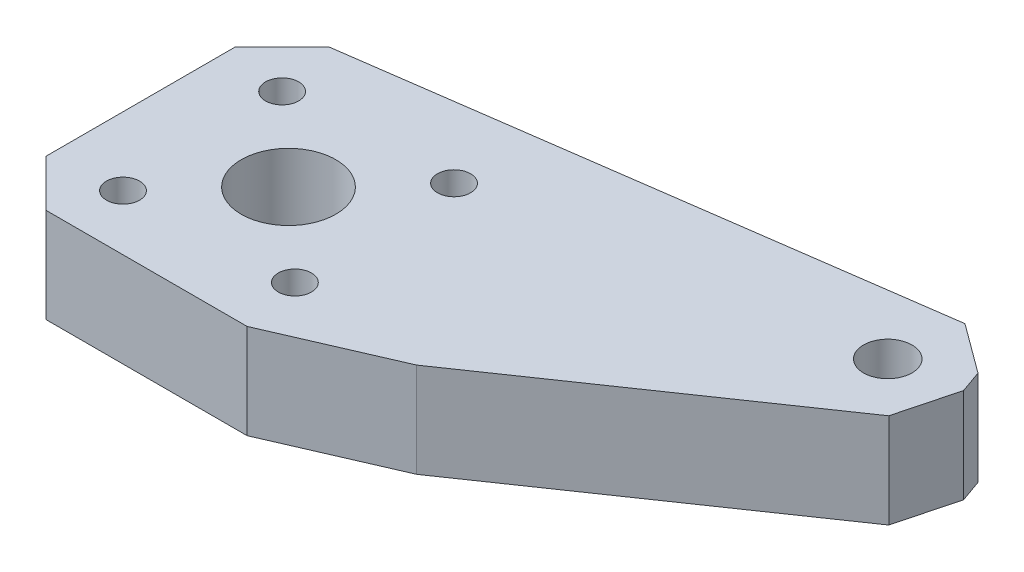
SolidWorks part; units mm, degrees
ref_plane "前视基准面" through (0, 0, 0) normal (0, 0, 1) x (1, 0, 0)
ref_plane "上视基准面" through (0, 0, 0) normal (0, 1, 0) x (1, 0, 0)
ref_plane "右视基准面" through (0, 0, 0) normal (1, 0, 0) x (0, 0, -1)
sketch "草图1" plane through (0, 0, 0) normal (0, 1, 0) x (1, 0, 0)
  line L0 (0, 0) -> (-3.9598, 3.9598)
  line L1 (-3.9598, 3.9598) -> (-3.9598, 19.9598)
  line L2 (-3.9598, 19.9598) -> (0, 23.9196)
  line L3 (0, 23.9196) -> (47.1368, 30.5442)
  line L4 (47.1368, 30.5442) -> (51.3094, 27.4747)
  line L5 (51.3094, 27.4747) -> (51.9765, 25.5893)
  line L6 (51.9765, 25.5893) -> (50.6628, 20.5786)
  line L7 (50.6628, 20.5786) -> (26.999, 4.3394)
  line L8 (26.999, 4.3394) -> (17, 0)
  line L9 (17, 0) -> (0, 0)
  line L10 (51.6429, 26.532) -> (46.4579, 24.6974) construction
  line L11 (-3.9598, 11.9598) -> (21.0402, 11.9598) construction
  line L12 (-1.9799, 21.9397) -> (2.8765, 17.0833) construction
  circle A0 centre (8.5402, 11.9598) radius 4
  circle A1 centre (46.4579, 24.6974) radius 2.05
  circle A2 centre (1.275, 18.6848) radius 1.4
  circle A3 centre (15.2652, 19.225) radius 1.4
  circle A4 centre (15.8054, 5.2348) radius 1.4
  circle A5 centre (1.8152, 4.6946) radius 1.4
  point P31 (8.5402, 11.9598)
  dimension "D15" = 40
  dimension "D17" = 12.5
  dimension "D20" = 4.1
  dimension "D21" = 8
  dimension "D22" = 9.9
  dimension "D23" = 2.8
  dimension "D2" = 16
  dimension "D3" = 5.6
  dimension "D4" = 5.6
  dimension "D5" = 17
  dimension "D6" = 47.6
  dimension "D7" = 10.9
  dimension "D8" = 28.7
  dimension "D9" = 5.18
  dimension "D10" = 2
  dimension "D11" = 5.18
  dimension "D12" = 45
  dimension "D13" = 45
  dimension "D14" = 45
  dimension "D16" = 143
  dimension "D18" = 5.5
  dimension "D19" = 169
  dimension "D24" = 4
extrude "凸台-拉伸1" add sketch "草图1" along normal blind 8
sketch "草图2" plane through (0, 0, 0) normal (0, -1, 0) x (1, 0, 0)
  circle A0 centre (8.5402, -11.9598) radius 7.5
  dimension "D1" = 15
